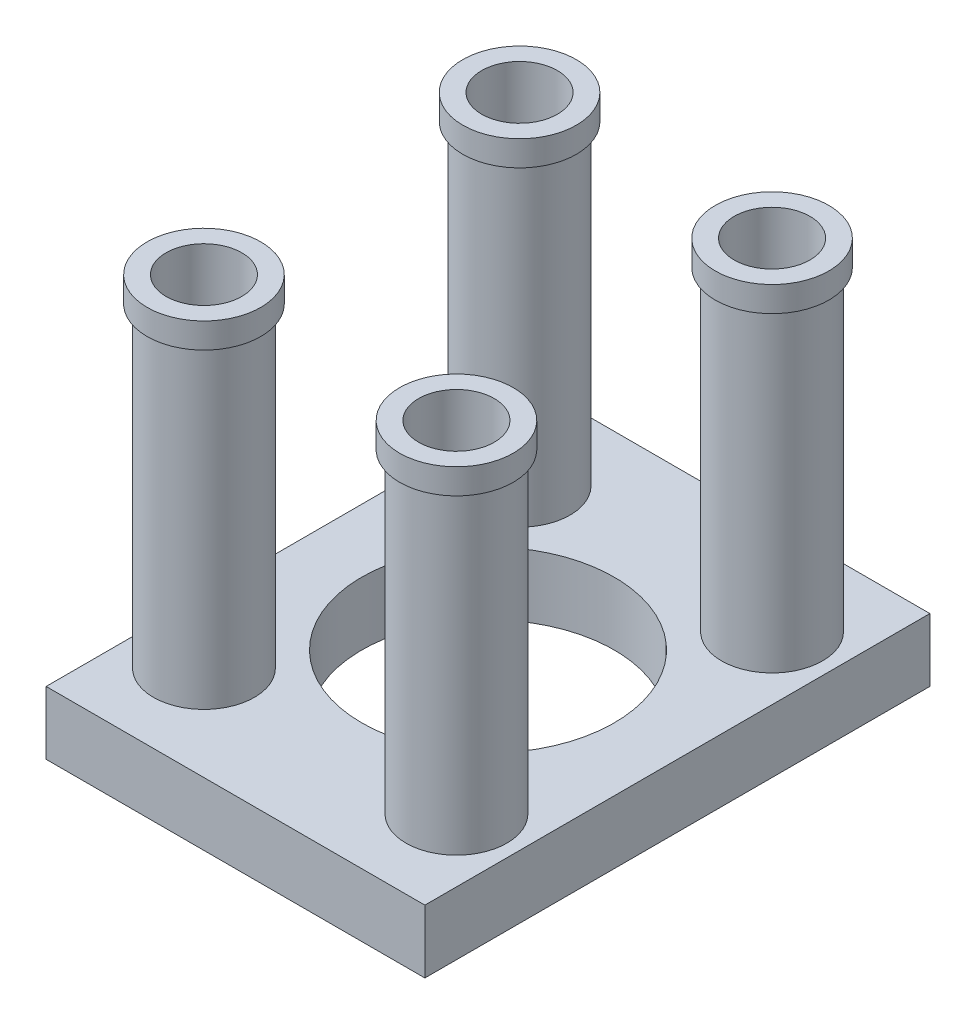
SolidWorks part; units mm, degrees
ref_plane "Front Plane" through (0, 0, 0) normal (0, 0, 1) x (1, 0, 0)
ref_plane "Top Plane" through (0, 0, 0) normal (0, 1, 0) x (1, 0, 0)
ref_plane "Right Plane" through (0, 0, 0) normal (1, 0, 0) x (0, 0, -1)
sketch "Sketch1" plane through (0, 0, 0) normal (0, 1, 0) x (1, 0, 0)
  line L1 (-19.05, 25.4) -> (19.05, 25.4)
  line L2 (-19.05, 25.4) -> (-19.05, -25.4)
  line L3 (-19.05, -25.4) -> (19.05, -25.4)
  line L4 (19.05, 25.4) -> (19.05, -25.4)
  dimension "D1" = 50.8
  dimension "D2" = 38.1
  dimension "D3" = 19.05
  dimension "D4" = 25.4
extrude "Boss-Extrude1" add sketch "Sketch1" along normal blind 6.35
sketch "Sketch2" plane through (0, 6.35, 0) normal (0, 1, 0) x (1, 0, 0)
  circle A0 centre (-12.7, 15.875) radius 5.08
  circle A1 centre (12.7, 15.875) radius 5.08
  circle A2 centre (12.7, -15.875) radius 5.08
  circle A3 centre (-12.7, -15.875) radius 5.08
  dimension "D5" = 10.16
  dimension "D1" = 15.875
  dimension "D2" = 12.7
  dimension "D3" = 12.7
  dimension "D4" = 15.875
extrude "Boss-Extrude2" add sketch "Sketch2" along normal blind 31.75
sketch "Sketch5" plane through (0, 6.35, 0) normal (0, 1, 0) x (1, 0, 0)
  circle A0 centre (0, 0) radius 12.7
  dimension "D1" = 25.4
extrude "Cut-Extrude1" cut sketch "Sketch5" against normal through all
sketch "Sketch6" plane through (0, 38.1, 0) normal (0, 1, 0) x (1, 0, 0)
  circle A0 centre (-12.7, 15.875) radius 3.81
  circle A1 centre (12.7, 15.875) radius 3.81
  circle A2 centre (12.7, -15.875) radius 3.81
  circle A3 centre (-12.7, -15.875) radius 3.81
  dimension "D1" = 7.62
extrude "Cut-Extrude2" cut sketch "Sketch6" against normal through all
sketch "Sketch7" plane through (0, 38.1, 0) normal (0, 1, 0) x (1, 0, 0)
  circle A0 centre (-12.7, 15.875) radius 5.715
  circle A1 centre (-12.7, -15.875) radius 5.715
  circle A2 centre (12.7, -15.875) radius 5.715
  circle A3 centre (12.7, 15.875) radius 5.715
  circle A4 centre (-12.7, 15.875) radius 3.81
  circle A5 centre (12.7, 15.875) radius 3.81
  circle A6 centre (12.7, -15.875) radius 3.81
  circle A7 centre (-12.7, -15.875) radius 3.81
  dimension "D1" = 11.43
extrude "Boss-Extrude3" add sketch "Sketch7" along normal blind 2.54
